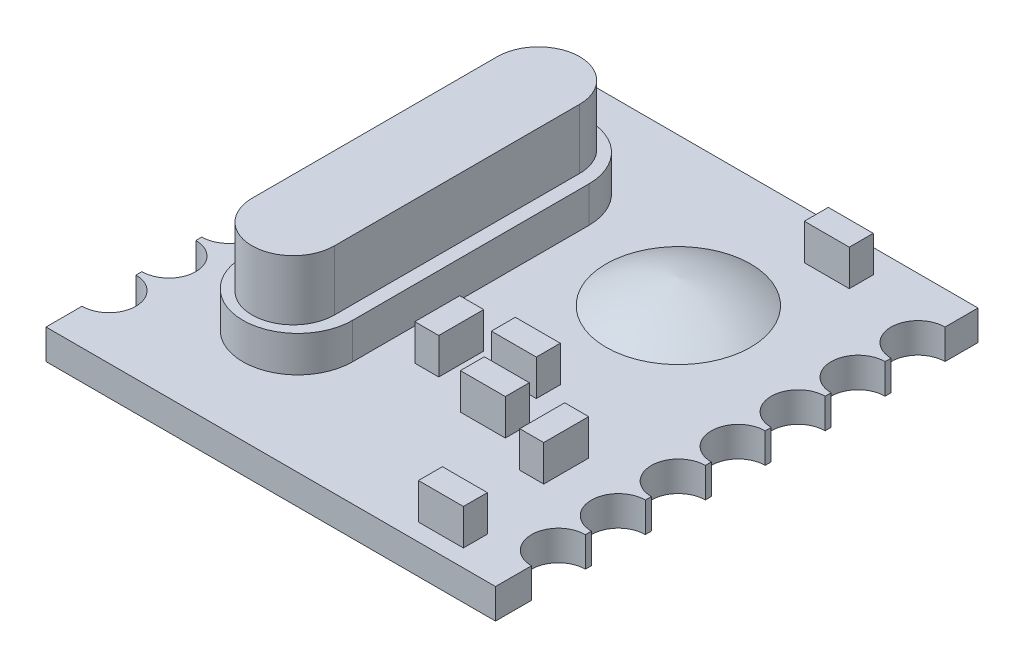
SolidWorks part; units mm, degrees
ref_plane "Front" through (0, 0, 0) normal (0, 0, 1) x (1, 0, 0)
ref_plane "Top" through (0, 0, 0) normal (0, 1, 0) x (1, 0, 0)
ref_plane "Right" through (0, 0, 0) normal (1, 0, 0) x (0, 0, -1)
sketch "Sketch1" plane through (0, 0, 0) normal (0, 1, 0) x (1, 0, 0)
  line L1 (-7.5, -8.05) -> (7.5, -8.05)
  line L2 (-7.5, -8.05) -> (-7.5, 8.05)
  line L3 (-7.5, 8.05) -> (7.5, 8.05)
  line L4 (7.5, -8.05) -> (7.5, 8.05)
  line L5 (-7.5, -8.05) -> (7.5, 8.05) construction
  line L6 (-7.5, 8.05) -> (7.5, -8.05) construction
  point P0 (0, 0)
  dimension "D1" = 16.1
  dimension "D2" = 15
extrude "Boss-Extrude1" add sketch "Sketch1" along normal blind 1
sketch "Sketch2" plane through (0, 1, 0) normal (0, 1, 0) x (1, 0, 0)
  line L0 (-7.5, 8.05) -> (-7.5, -8.05) construction
  line L1 (7.5, 8.05) -> (-7.5, 8.05) construction
  line L2 (-7.5, 5.15) -> (-7.5, 6.95)
  arc A0 (-7.5, 6.95) -> (-7.5, 5.15) centre (-7.5, 6.05) cw
  dimension "D1" = 0.9
  dimension "D2" = 2
extrude "Cut-Extrude2" cut sketch "Sketch2" against normal blind 1
pattern_linear "LPattern1" count 7 spacing 2 along (0, 0, 1) of "Cut-Extrude2"
mirror "Mirror1" about plane through (0, 0, 0) normal (1, 0, 0) of "LPattern1", "Cut-Extrude2"
sketch "Sketch3" plane through (0, 1, 0) normal (0, 1, 0) x (1, 0, 0)
  line L0 (-3.2085, 3.9406) -> (-3.2085, -3.9406) construction
  line L1 (-1.3781, 3.9406) -> (-1.3781, -3.9406)
  line L2 (-5.0388, 3.9406) -> (-5.0388, -3.9406)
  line L5 (-50, 0) -> (50, 0) construction
  arc A0 (-1.3781, 3.9406) -> (-5.0388, 3.9406) centre (-3.2085, 3.9406) ccw
  arc A1 (-5.0388, -3.9406) -> (-1.3781, -3.9406) centre (-3.2085, -3.9406) ccw
  point P2 (-3.2085, 0)
extrude "Boss-Extrude2" add sketch "Sketch3" along normal blind 1.2
ref_plane "Plane1" through (-3.2085, 0, 0) normal (-1, 0, 0) x (0, 0, 1)
sketch "Sketch4" plane through (0, 2.2, 0) normal (0, 1, 0) x (1, 0, 0)
  line L0 (-3.2085, 4.0914) -> (-3.2085, -4.0914) construction
  line L1 (-1.8335, 4.0914) -> (-1.8335, -4.0914)
  line L2 (-4.5835, 4.0914) -> (-4.5835, -4.0914)
  line L3 (-50, 0) -> (50, 0) construction
  line L4 (-3.2085, 0.66) -> (-3.2085, -0.66) construction
  arc A0 (-1.8335, 4.0914) -> (-4.5835, 4.0914) centre (-3.2085, 4.0914) ccw
  arc A1 (-4.5835, -4.0914) -> (-1.8335, -4.0914) centre (-3.2085, -4.0914) ccw
  point P2 (-3.2085, 0)
  dimension "D1" = 2.75
extrude "Boss-Extrude3" add sketch "Sketch4" along normal blind 2
sketch "Sketch5" plane through (0, 1, 0) normal (0, 1, 0) x (1, 0, 0)
  line L1 (-0.3015, -1.4427) -> (0.4985, -1.4427)
  line L2 (-0.3015, -1.4427) -> (-0.3015, -2.9427)
  line L3 (-0.3015, -2.9427) -> (0.4985, -2.9427)
  line L4 (0.4985, -1.4427) -> (0.4985, -2.9427)
  line L5 (1.2489, -1.138) -> (2.7489, -1.138)
  line L6 (1.2489, -1.138) -> (1.2489, -1.938)
  line L7 (1.2489, -1.938) -> (2.7489, -1.938)
  line L8 (2.7489, -1.138) -> (2.7489, -1.938)
  line L9 (1.8734, -2.7961) -> (3.3734, -2.7961)
  line L10 (1.8734, -2.7961) -> (1.8734, -3.5961)
  line L11 (1.8734, -3.5961) -> (3.3734, -3.5961)
  line L12 (3.3734, -2.7961) -> (3.3734, -3.5961)
  line L13 (4.5436, -2.7852) -> (5.3436, -2.7852)
  line L14 (4.5436, -2.7852) -> (4.5436, -4.2852)
  line L15 (4.5436, -4.2852) -> (5.3436, -4.2852)
  line L16 (5.3436, -2.7852) -> (5.3436, -4.2852)
  line L17 (4.3498, -6.6721) -> (5.8498, -6.6721)
  line L18 (4.3498, -6.6721) -> (4.3498, -7.4721)
  line L19 (4.3498, -7.4721) -> (5.8498, -7.4721)
  line L20 (5.8498, -6.6721) -> (5.8498, -7.4721)
  line L21 (3.2946, 7.2601) -> (4.7946, 7.2601)
  line L22 (3.2946, 7.2601) -> (3.2946, 6.4601)
  line L23 (3.2946, 6.4601) -> (4.7946, 6.4601)
  line L24 (4.7946, 7.2601) -> (4.7946, 6.4601)
  dimension "D1" = 0.8
  dimension "D2" = 1.5
extrude "Boss-Extrude4" add sketch "Sketch5" along normal blind 1.2
ref_plane "Plane2" through (0, 0, -3.05) normal (0, 0, -1) x (-1, 0, 0)
ref_plane "Plane3" through (2.5, 0, 0) normal (1, 0, 0) x (0, 0, -1)
ref_axis "Axis1" through (2.5, -0.05, -3.05) along (0, 1, 0)
sketch "Sketch8" plane through (0, 0, -3.05) normal (0, 0, -1) x (-1, 0, 0)
  line L0 (-2.5, 1.0686) -> (-2.5, 1.8686)
  line L1 (-2.5, 1.0686) -> (-4.9117, 1.0686)
  line L2 (-2.5, -0.05) -> (-2.5, 1.05) construction
  spline S0 degree 2 poles (-2.5, 1.8686) (-3.7906, 1.7262) (-4.9117, 1.0686) knots 0 0 0 1 1 1
  dimension "D1" = 0.8
revolve "Revolve1" add sketch "Sketch8" angle 360 about axis through (2.5, -0.05, -3.05) along (0, 1, 0)
